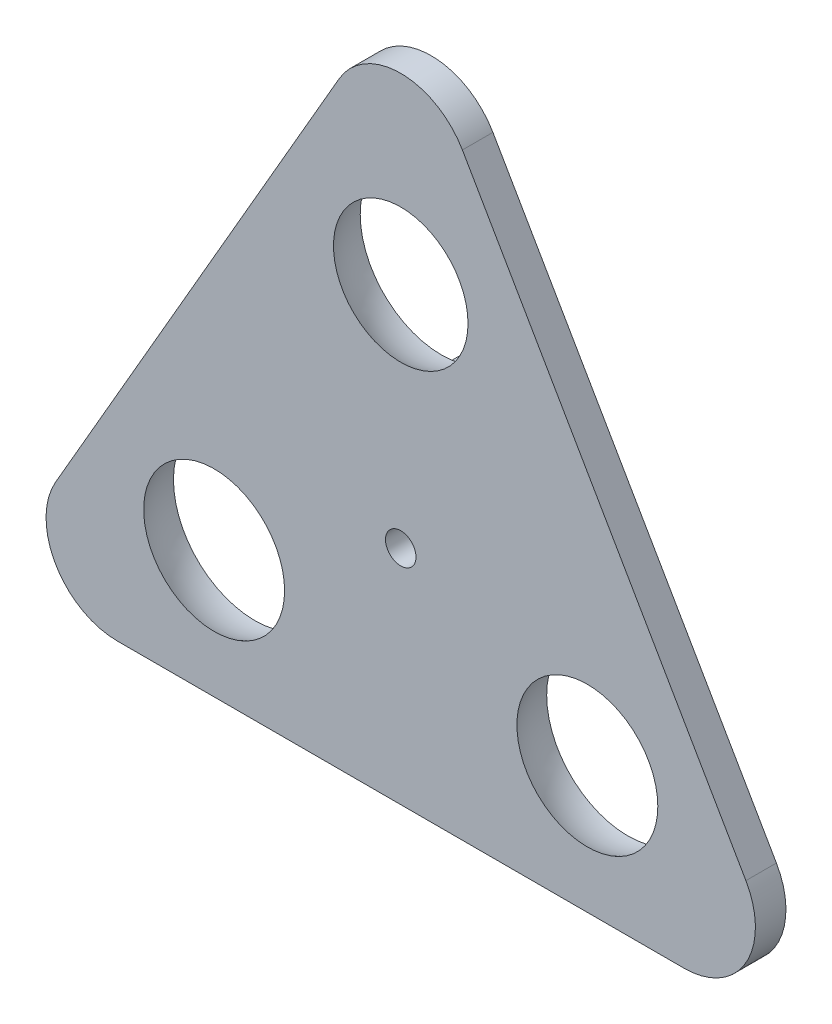
SolidWorks part; units mm, degrees
ref_plane "Front Plane" through (0, 0, 0) normal (0, 0, 1) x (1, 0, 0)
ref_plane "Top Plane" through (0, 0, 0) normal (0, 1, 0) x (1, 0, 0)
ref_plane "Right Plane" through (0, 0, 0) normal (1, 0, 0) x (0, 0, -1)
sketch "Sketch1" plane through (0, 0, 0) normal (0, 0, 1) x (1, 0, 0)
  line L0 (0, 0) -> (80, 0)
  line L1 (80, 0) -> (40, 69.282)
  line L2 (0, 0) -> (40, 69.282)
  dimension "D1" = 80
  dimension "D2" = 60
  dimension "D3" = 60
  dimension "D4" = 60
extrude "Boss-Extrude1" add sketch "Sketch1" along normal blind 3
fillet "Fillet4" radius 7 1 edges at (0, 0, 1.5)
fillet "Fillet5" radius 7 1 edges at (80, 0, 1.5)
fillet "Fillet6" radius 7 1 edges at (40, 69.282, 1.5)
sketch "Sketch6" plane through (0, 0, 0) normal (0, 0, -1) x (-1, 0, 0)
  circle A0 centre (-40, 44.282) radius 10
  circle A1 centre (-58.3494, 12.5) radius 10
  circle A2 centre (-21.6506, 12.5) radius 10
  dimension "D1" = 20
  dimension "D2" = 20
  dimension "D3" = 20
extrude "Boss-Extrude2" add sketch "Sketch6" along normal blind 1
sketch "Sketch7" plane through (0, 0, -1.5) normal (0, 0, -1) x (-1, 0, 0)
  line L0 (-40, 52.282) -> (-40, 36.282)
  circle A0 centre (-40, 44.282) radius 10 construction
  arc A1 (-40, 52.282) -> (-40, 36.282) centre (-40, 44.282) cw
  dimension "D9" = 8
  dimension "D1" = 16
  dimension "D2" = 8
revolve "Cut-Revolve2" cut sketch "Sketch7" angle 360 about L0
sketch "Sketch8" plane through (0, 0, -1) normal (0, 0, -1) x (-1, 0, 0)
  line L0 (-58.3494, 20.5) -> (-58.3494, 4.5)
  circle A0 centre (-58.3494, 12.5) radius 10 construction
  arc A2 (-58.3494, 20.5) -> (-58.3494, 4.5) centre (-58.3494, 12.5) cw
  dimension "D3" = 8
  dimension "D1" = 16
  dimension "D2" = 8
revolve "Cut-Revolve3" cut sketch "Sketch8" angle 360 about L0
sketch "Sketch9" plane through (0, 0, -1) normal (0, 0, -1) x (-1, 0, 0)
  line L0 (-21.6506, 20.5) -> (-21.6506, 4.5)
  circle A0 centre (-21.6506, 12.5) radius 10 construction
  arc A1 (-21.6506, 20.5) -> (-21.6506, 4.5) centre (-21.6506, 12.5) cw
  dimension "D3" = 8
  dimension "D1" = 16
  dimension "D2" = 8
revolve "Cut-Revolve4" cut sketch "Sketch9" angle 360 about L0
sketch "Sketch10" plane through (0, 0, 0) normal (0, 0, -1) x (-1, 0, 0)
  line L0 (-12.1244, 0) -> (-67.8756, 0) construction
  line L8 (-37, 29.3288) -> (-34, 29.3288)
  line L9 (-37, 29.3288) -> (-37, 14.3288)
  line L10 (-37, 14.3288) -> (-34, 14.3288)
  line L11 (-34, 29.3288) -> (-34, 14.3288)
  line L12 (-43, 29.3288) -> (-46, 29.3288)
  line L13 (-43, 29.3288) -> (-43, 14.3288)
  line L14 (-43, 14.3288) -> (-46, 14.3288)
  line L15 (-46, 29.3288) -> (-46, 14.3288)
  point P0 (-40, 20.2073)
  point P5 (-40, 0)
  point P14 (-40, 0)
  point P15 (-40, 0)
  dimension "D1" = 3
  dimension "D2" = 0
  dimension "D3" = 3
  dimension "D4" = 3
  dimension "D5" = 3
  dimension "D7" = 15
  dimension "D8" = 15
extrude "Boss-Extrude3" add sketch "Sketch10" along normal blind 9
sketch "Sketch11" plane through (34, 0, 0) normal (-1, 0, 0) x (0, 0, 1)
  line L0 (-9, 14.3288) -> (0, 14.3288) construction
  line L1 (-9, 29.3288) -> (0, 29.3288) construction
  line L2 (-9, 14.3288) -> (-9, 29.3288) construction
  circle A0 centre (-4.5, 24.8288) radius 1.5
  circle A1 centre (-4.5, 18.8288) radius 1.5
  dimension "D1" = 4.5
  dimension "D2" = 4.5
  dimension "D3" = 3
  dimension "D4" = 3
  dimension "D5" = 4.5
  dimension "D6" = 4.5
extrude "Cut-Extrude4" cut sketch "Sketch11" against normal blind 14
sketch "Sketch13" plane through (0, 0, 3) normal (0, 0, 1) x (1, 0, 0)
  line L2 (12.1244, 0) -> (67.8756, 0) construction
  line L4 (37, 29.3288) -> (37, 14.3288) construction
  circle A3 centre (40, 21.8288) radius 1.5
  point P0 (40, 0)
  point P3 (37, 21.8288)
  dimension "D1" = 3
  dimension "D2" = 0
  dimension "D3" = 0
extrude "Cut-Extrude5" cut sketch "Sketch13" against normal blind 10
